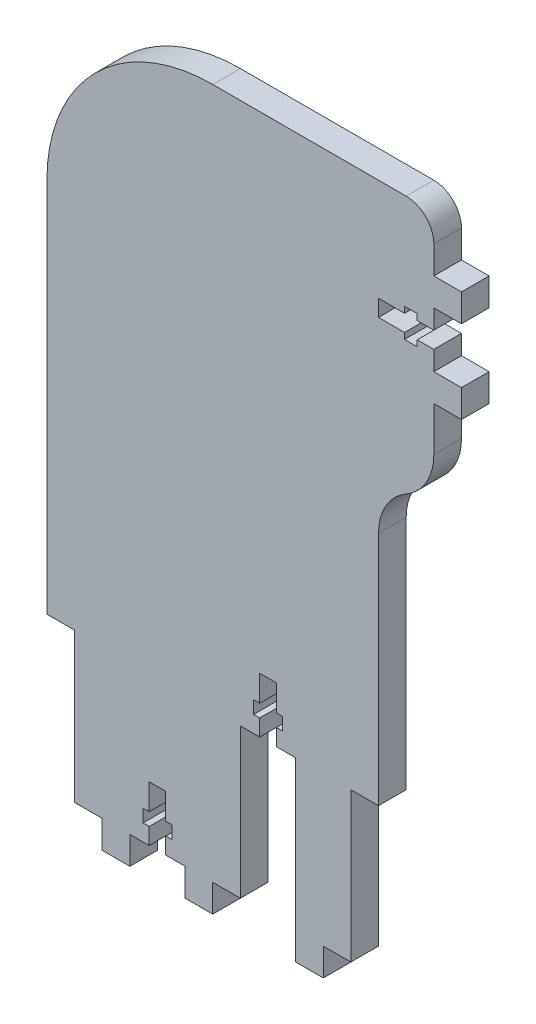
SolidWorks part; units mm, degrees
ref_plane "Plan de face" through (0, 0, 0) normal (0, 0, 1) x (1, 0, 0)
ref_plane "Plan de dessus" through (0, 0, 0) normal (0, 1, 0) x (1, 0, 0)
ref_plane "Plan de droite" through (0, 0, 0) normal (1, 0, 0) x (0, 0, -1)
sketch "Esquisse1" plane through (0, 0, 0) normal (0, 0, 1) x (1, 0, 0)
  line L0 (-10, 0) -> (-10, -42.6795)
  line L1 (-40, -69.6795) -> (-40, -74.6795)
  line L2 (-40, -74.6795) -> (-45, -74.6795)
  line L3 (-45, -74.6795) -> (-45, -69.6795)
  line L4 (-48.5, -66.6795) -> (-47.4, -66.6795)
  line L5 (-47.4, -66.6795) -> (-47.4, -64.3795)
  line L6 (-47.4, -64.3795) -> (-48.5, -64.3795)
  line L7 (-48.5, -64.3795) -> (-48.5, -59.6795)
  line L8 (-48.5, -59.6795) -> (-51.5, -59.6795)
  line L9 (-51.5, -59.6795) -> (-51.5, -64.3795)
  line L10 (-51.5, -64.3795) -> (-52.6, -64.3795)
  line L11 (-52.6, -64.3795) -> (-52.6, -66.6795)
  line L12 (-52.6, -66.6795) -> (-51.5, -66.6795)
  line L13 (-45, -69.6795) -> (-48.5, -69.6795)
  line L14 (-55, -74.6795) -> (-60, -74.6795)
  line L15 (-60, -74.6795) -> (-60, -69.6795)
  line L16 (-60, -69.6795) -> (-65, -69.6795)
  line L17 (-35, -69.6795) -> (-40, -69.6795)
  line L18 (-70, -42.6795) -> (-70, 25.3205)
  line L19 (0, 50.3205) -> (0, 45.3205)
  line L20 (0, 45.3205) -> (5, 45.3205)
  line L21 (5, 45.3205) -> (5, 40.3205)
  line L22 (-48.5, -69.6795) -> (-48.5, -66.6795)
  line L23 (-3, 36.8205) -> (-3, 37.9205)
  line L24 (-3, 37.9205) -> (-5.3, 37.9205)
  line L25 (-5.3, 37.9205) -> (-5.3, 36.8205)
  line L26 (-5.3, 36.8205) -> (-10, 36.8205)
  line L27 (-10, 36.8205) -> (-10, 33.8205)
  line L28 (-10, 33.8205) -> (-5.3, 33.8205)
  line L29 (-5.3, 33.8205) -> (-5.3, 32.7205)
  line L30 (-5.3, 32.7205) -> (-3, 32.7205)
  line L31 (-3, 32.7205) -> (-3, 33.8205)
  line L32 (-55, -74.6795) -> (-55, -69.6795)
  line L33 (5, 30.3205) -> (5, 25.3205)
  line L34 (5, 25.3205) -> (0, 25.3205)
  line L35 (0, 25.3205) -> (0, 17.3205)
  line L36 (-55, -69.6795) -> (-51.5, -69.6795)
  line L37 (-51.5, -69.6795) -> (-51.5, -66.6795)
  line L38 (5, 30.3205) -> (0, 30.3205)
  line L39 (0, 30.3205) -> (0, 33.8205)
  line L40 (0, 33.8205) -> (-3, 33.8205)
  line L41 (5, 40.3205) -> (0, 40.3205)
  line L42 (0, 40.3205) -> (0, 36.8205)
  line L43 (0, 36.8205) -> (-3, 36.8205)
  line L44 (0, 10) -> (0, 0) construction
  line L45 (-40, 55.3205) -> (-5, 55.3205)
  line L46 (-65, -69.6795) -> (-65, -42.6795)
  line L47 (-65, -42.6795) -> (-70, -42.6795)
  line L49 (-35, -69.6795) -> (-35, -42.6795)
  line L50 (-28.5, -39.6795) -> (-27.4, -39.6795)
  line L51 (-27.4, -39.6795) -> (-27.4, -37.3795)
  line L52 (-27.4, -37.3795) -> (-28.5, -37.3795)
  line L53 (-28.5, -37.3795) -> (-28.5, -32.6795)
  line L54 (-28.5, -32.6795) -> (-31.5, -32.6795)
  line L55 (-31.5, -32.6795) -> (-31.5, -37.3795)
  line L56 (-31.5, -37.3795) -> (-32.6, -37.3795)
  line L57 (-32.6, -37.3795) -> (-32.6, -39.6795)
  line L58 (-32.6, -39.6795) -> (-31.5, -39.6795)
  line L59 (-25, -42.6795) -> (-28.5, -42.6795)
  line L60 (-28.5, -42.6795) -> (-28.5, -39.6795)
  line L61 (-35, -42.6795) -> (-31.5, -42.6795)
  line L62 (-31.5, -42.6795) -> (-31.5, -39.6795)
  line L63 (-25, -42.6795) -> (-25, -74.6795)
  line L64 (-25, -74.6795) -> (-20, -74.6795)
  line L65 (-20, -74.6795) -> (-20, -69.6795)
  line L66 (-20, -69.6795) -> (-15, -69.6795)
  line L67 (-15, -69.6795) -> (-15, -42.6795)
  line L68 (-15, -42.6795) -> (-10, -42.6795)
  arc A0 (-5, 8.6603) -> (-10, 0) centre (0, 0) ccw
  arc A1 (0, 17.3205) -> (-5, 8.6603) centre (-10, 17.3205) cw
  arc A3 (-70, 25.3205) -> (-40, 55.3205) centre (-40, 25.3205) cw
  arc A4 (0, 50.3205) -> (-5, 55.3205) centre (-5, 50.3205) ccw
  point P79 (0, 0)
  point P84 (-17.5, -69.6795)
  point P86 (0, 0)
  point P87 (-70, -71.1777)
  point P88 (0, 0)
  point P89 (0, 0)
  dimension "D1" = 5
  dimension "D9" = 5
  dimension "D10" = 60
  dimension "D17" = 5
  dimension "D18" = 5
  dimension "D19" = 5
  dimension "D21" = 130
  dimension "D11" = 10
  dimension "D13" = 10
  dimension "D14" = 5
  dimension "D16" = 30
  dimension "D2" = 5
  dimension "D3" = 2.3
  dimension "D4" = 3
  dimension "D5" = 3
  dimension "D6" = 4.7
  dimension "D7" = 1.1
  dimension "D8" = 3.5
  dimension "D12" = 8
  dimension "D15" = 5
  dimension "D20" = 27
extrude "Boss.-Extru.1" add sketch "Esquisse1" along normal blind 5
